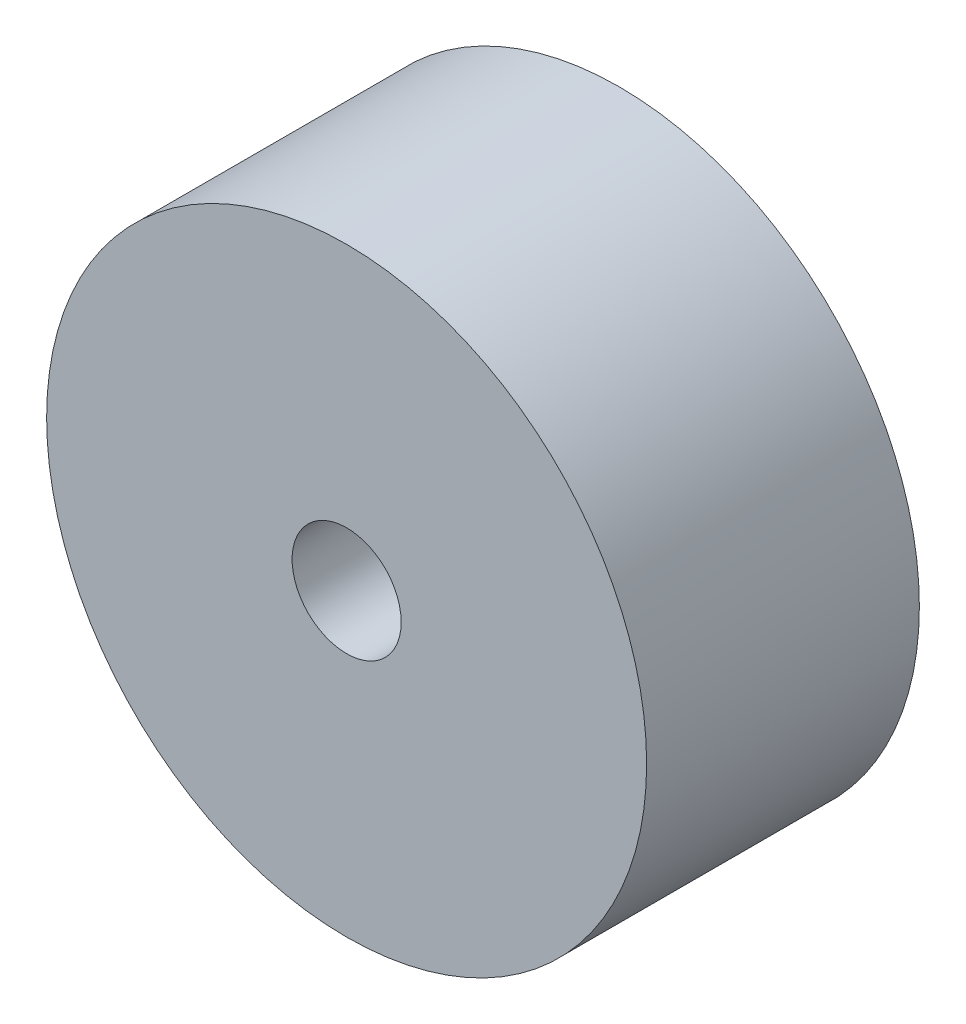
SolidWorks part; units mm, degrees
ref_plane "Front Plane" through (0, 0, 0) normal (0, 0, 1) x (1, 0, 0)
ref_plane "Top Plane" through (0, 0, 0) normal (0, 1, 0) x (1, 0, 0)
ref_plane "Right Plane" through (0, 0, 0) normal (1, 0, 0) x (0, 0, -1)
sketch "Sketch1" plane through (0, 0, 0) normal (0, 0, 1) x (1, 0, 0)
  circle A0 centre (0, 0) radius 27.5
  dimension "D1" = 55
extrude "Boss-Extrude1" add sketch "Sketch1" along normal blind 25
sketch "Sketch2" plane through (0, 0, 25) normal (0, 0, 1) x (1, 0, 0)
  circle A0 centre (0, 0) radius 5
  dimension "D1" = 10
extrude "Cut-Extrude1" cut sketch "Sketch2" against normal blind 25
